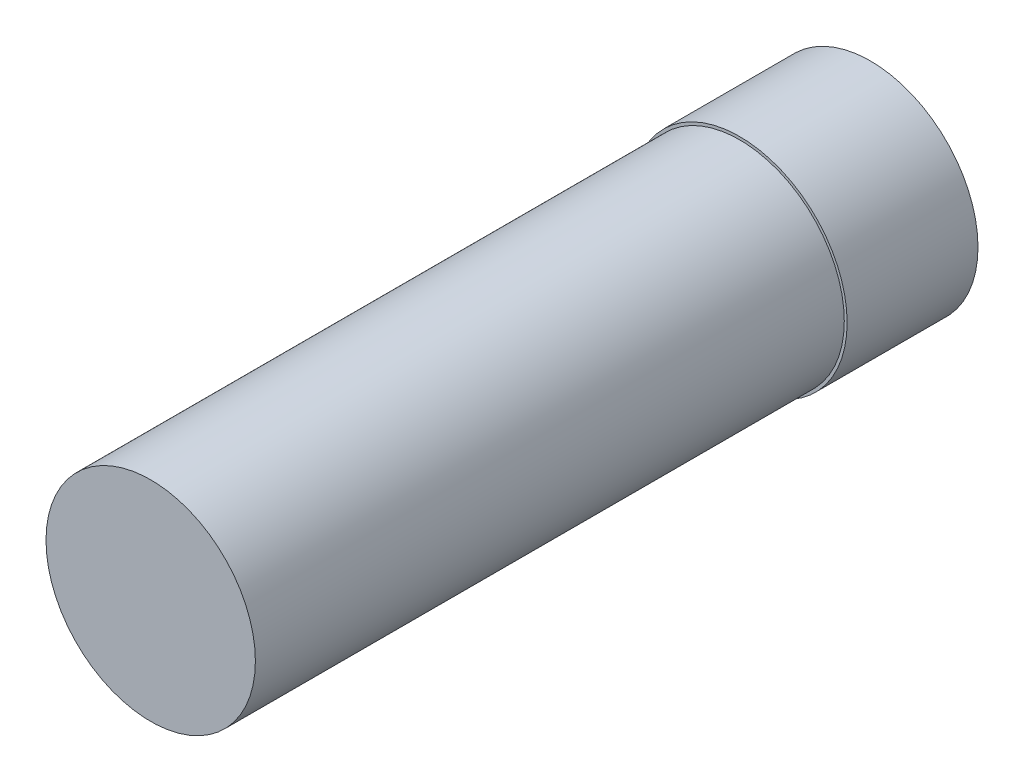
SolidWorks part; units mm, degrees
ref_plane "정면" through (0, 0, 0) normal (0, 0, 1) x (1, 0, 0)
ref_plane "윗면" through (0, 0, 0) normal (0, 1, 0) x (1, 0, 0)
ref_plane "우측면" through (0, 0, 0) normal (1, 0, 0) x (0, 0, -1)
sketch "스케치1" plane through (0, 0, 0) normal (0, 0, 1) x (1, 0, 0)
  circle A0 centre (0, 0) radius 2.465
  dimension "D1" = 4.93
extrude "보스-돌출1" add sketch "스케치1" along normal blind 3
sketch "스케치2" plane through (0, 0, 3) normal (0, 0, 1) x (1, 0, 0)
  circle A0 centre (0, 0) radius 2.4
  dimension "D1" = 4.8
extrude "보스-돌출2" add sketch "스케치2" along normal blind 13.5
sketch "스케치3" plane through (0, 0, 16.5) normal (0, 0, 1) x (1, 0, 0)
  circle A0 centre (0, 0) radius 2.45
  dimension "D1" = 4.9
